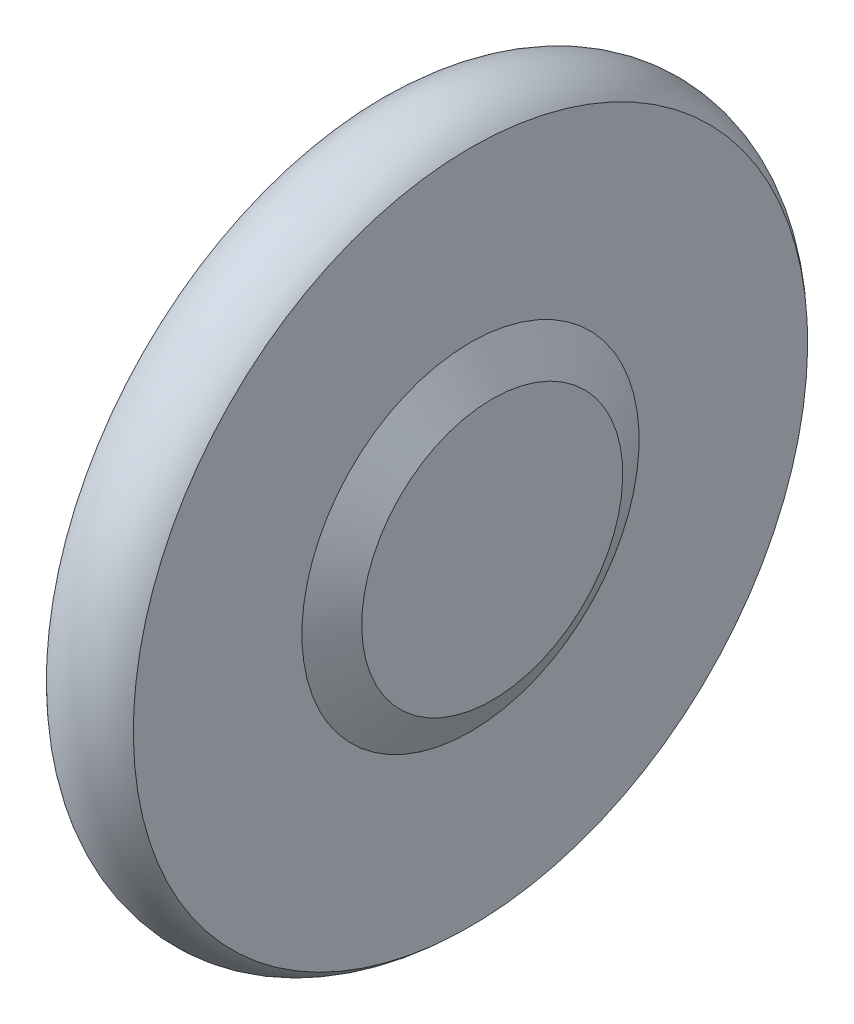
SolidWorks part; units mm, degrees
ref_plane "前视基准面" through (0, 0, 0) normal (0, 0, 1) x (1, 0, 0)
ref_plane "上视基准面" through (0, 0, 0) normal (0, 1, 0) x (1, 0, 0)
ref_plane "右视基准面" through (0, 0, 0) normal (1, 0, 0) x (0, 0, -1)
sketch "草图1" plane through (0, 0, 0) normal (0, 0, 1) x (1, 0, 0)
  line L0 (0, 0) -> (20, 0)
  line L1 (20, 77.5) -> (20, 155)
  line L3 (0, 0) -> (-20, 0)
  line L4 (-20, 77.5) -> (-20, 155)
  line L6 (-20, 0) -> (-30, 0)
  line L7 (-30, 8) -> (-30, 60)
  line L8 (-30, 60) -> (-20, 77.5)
  line L9 (-30, 0) -> (-50, 0)
  line L10 (-50, 0) -> (-50, 8)
  line L11 (-50, 8) -> (-30, 8)
  line L12 (20, 0) -> (30, 0)
  line L13 (30, 0) -> (30, 60)
  line L14 (30, 60) -> (20, 77.5)
  arc A0 (-20, 155) -> (20, 155) centre (0, 135) cw
revolve "旋转1" add sketch "草图1" angle 360 about L3
